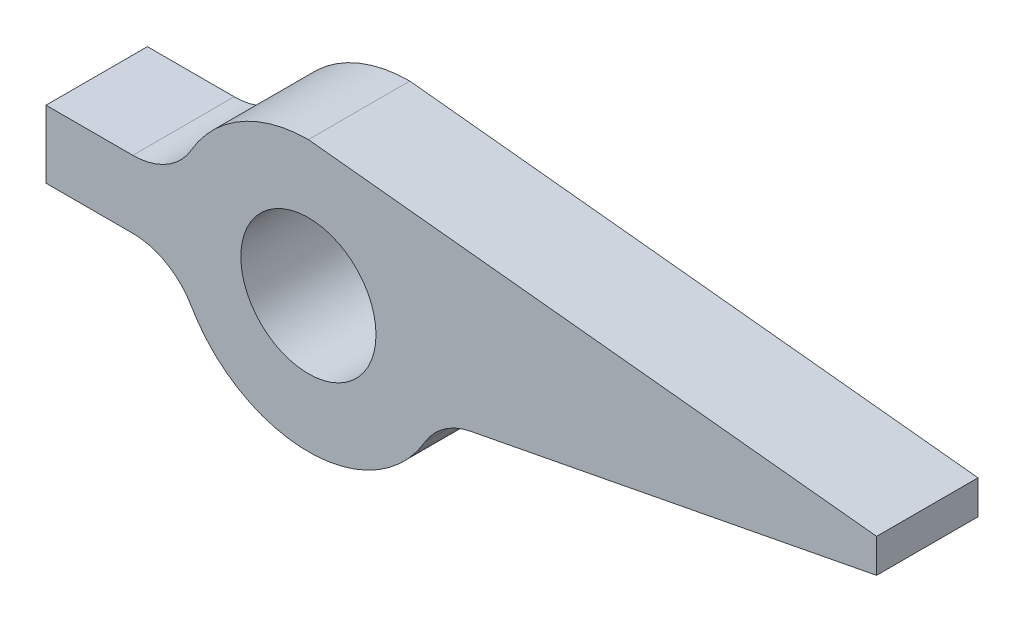
SolidWorks part; units mm, degrees
ref_plane "Front Plane" through (0, 0, 0) normal (0, 0, 1) x (1, 0, 0)
ref_plane "Top Plane" through (0, 0, 0) normal (0, 1, 0) x (1, 0, 0)
ref_plane "Right Plane" through (0, 0, 0) normal (1, 0, 0) x (0, 0, -1)
sketch "Sketch1" plane through (0, 0, 0) normal (0, 0, 1) x (1, 0, 0)
  line L6 (-2.8099, 17.7705) -> (-2.8099, 17.2705)
  line L7 (-2.8099, 17.2705) -> (-9.3194, 16.016)
  line L11 (-10.8444, 15.7221) -> (-11.2161, 15.6505)
  line L12 (-11.2161, 18.6505) -> (-2.8099, 17.7705)
  line L13 (-15.0981, 16.6505) -> (-15.0981, 17.1505)
  line L14 (-15.0981, 17.1505) -> (-13.1525, 17.1505)
  line L15 (-15.0981, 16.6505) -> (-15.0981, 16.1505)
  line L16 (-15.0981, 16.1505) -> (-13.1525, 16.1505)
  line L17 (-11.2161, 16.6505) -> (-11.2161, 16.1505)
  circle A2 centre (-11.2161, 16.6505) radius 1
  circle A3 centre (-11.2161, 16.6505) radius 2
extrude "Boss-Extrude1" add sketch "Sketch1" along normal blind 1.5
fillet "Fillet1" radius 1 1 edges at (-13.1525, 16.1505, 0.75)
fillet "Fillet2" radius 1 1 edges at (-13.1525, 17.1505, 0.75)
fillet "Fillet3" radius 1 1 edges at (-9.3194, 16.016, 0.75)
